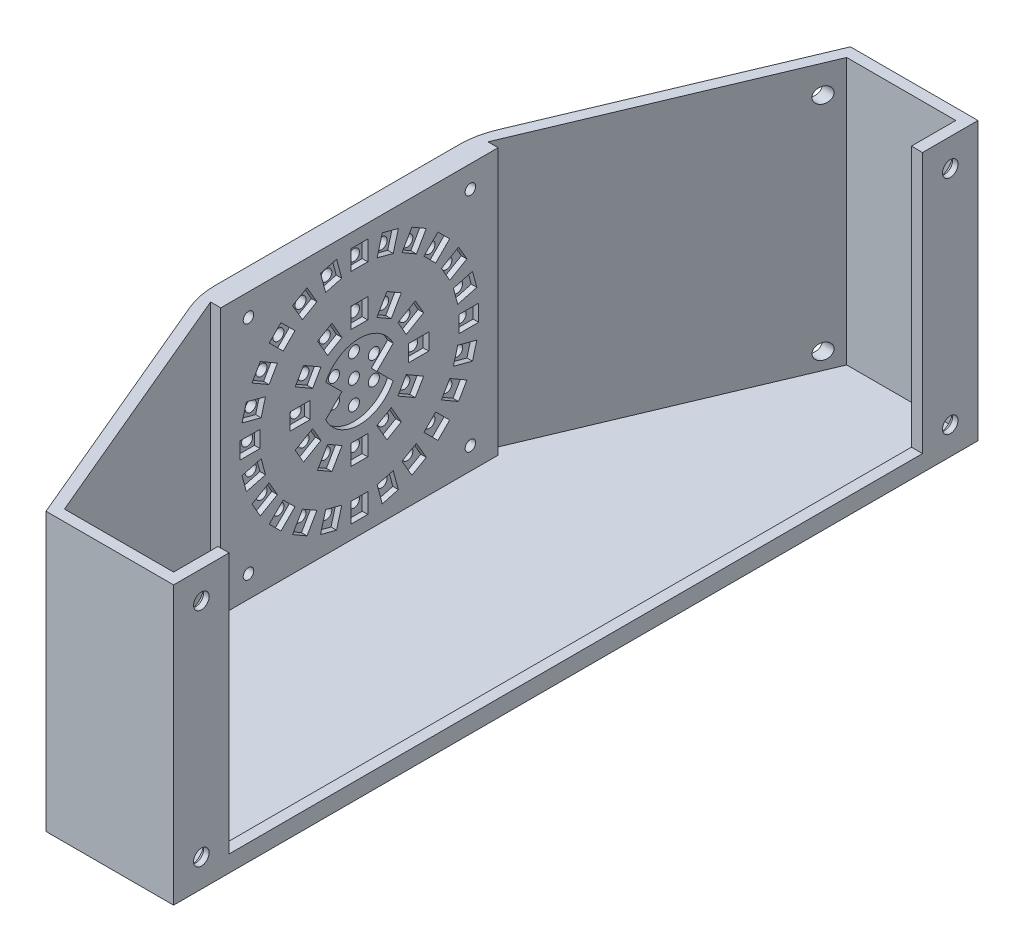
SolidWorks part; units mm, degrees
ref_plane "Спереди" through (0, 0, 0) normal (0, 0, 1) x (1, 0, 0)
ref_plane "Сверху" through (0, 0, 0) normal (0, 1, 0) x (1, 0, 0)
ref_plane "Справа" through (0, 0, 0) normal (1, 0, 0) x (0, 0, -1)
sketch "Эскиз1" plane through (0, 0, 0) normal (0, 1, 0) x (1, 0, 0)
  line L0 (0, 159.887) -> (0, 0) construction
  line L1 (0, 0) -> (281.7797, 0) construction
  line L2 (-60, -50) -> (-60, 50)
  line L3 (-20, -145) -> (20, -145)
  line L5 (-20, 145) -> (20, 145)
  line L6 (20, -145) -> (20, 145)
  line L7 (0, 145) -> (0, -145) construction
  line L8 (-435.8276, 0) -> (20, 0) construction
  line L9 (-60, 50) -> (-20, 145)
  line L10 (-60, -50) -> (-20, -145)
  point P10 (-60, 0)
  dimension "D1" = 290
  dimension "D2" = 40
  dimension "D3" = 100
  dimension "D4" = 80
extrude "Бобышка-Вытянуть1" add sketch "Эскиз1" along normal blind 4
sketch "Эскиз2" plane through (0, 0, 0) normal (0, 1, 0) x (1, 0, 0)
  line L1 (20, 145) -> (26, 145)
  line L2 (20, 145) -> (20, -145)
  line L3 (20, -145) -> (26, -145)
  line L4 (26, 145) -> (26, -145)
  dimension "D1" = 290
  dimension "D2" = 6
extrude "Бобышка-Вытянуть2" add sketch "Эскиз2" along normal blind 4
sketch "Эскиз17" plane through (0, 4, 0) normal (0, 1, 0) x (1, 0, 0)
  line L0 (-20, 145) -> (-60, 50)
  line L1 (-60, 50) -> (-60, -50)
  line L2 (-60, -50) -> (-20, -145)
  line L3 (-20, -145) -> (26, -145)
  line L4 (26, -145) -> (26, 145)
  line L5 (26, 145) -> (-20, 145)
extrude "Вытянуть-Тонкостенный1" add sketch "Эскиз17" along normal blind 96 thin thin type one direction reverse wall 4
sketch "Эскиз29" plane through (0, 100, 0) normal (0, 1, 0) x (1, 0, 0)
  line L1 (-60, 50) -> (-52, 50)
  line L2 (-60, 50) -> (-60, -50)
  line L3 (-60, -50) -> (-52, -50)
  line L4 (-52, 50) -> (-52, -50)
  dimension "D1" = 8
extrude "Бобышка-Вытянуть5" add sketch "Эскиз29" against normal blind 96
sketch "Эскиз20" plane through (-52, 0, 0) normal (1, 0, 0) x (0, 0, -1)
  line L0 (8.2314, 94.3113) -> (6.3873, 87.4288)
  line L1 (6.3, 52) -> (12.1612, 57.8612)
  line L10 (0, 0) -> (0, 100) construction
  line L12 (-48.7884, 52) -> (48.7884, 52) construction
  line L15 (-3, 95) -> (3, 95)
  line L16 (-3, 95) -> (-3, 87.8748)
  line L17 (-3, 87.8748) -> (3, 87.8748)
  line L18 (3, 95) -> (3, 87.8748)
  line L19 (0, 87.8748) -> (0, 95) construction
  line L20 (-3, 91.4374) -> (3, 91.4374) construction
  line L21 (8.2314, 94.3113) -> (14.027, 92.7584)
  line L22 (14.027, 92.7584) -> (12.1829, 85.8759)
  line L23 (6.3873, 87.4288) -> (12.1829, 85.8759)
  line L24 (18.9019, 90.7391) -> (15.3393, 84.5685)
  line L25 (18.9019, 90.7391) -> (24.0981, 87.7391)
  line L26 (24.0981, 87.7391) -> (20.5355, 81.5685)
  line L27 (15.3393, 84.5685) -> (20.5355, 81.5685)
  line L28 (28.2843, 84.5269) -> (23.246, 79.4886)
  line L29 (28.2843, 84.5269) -> (32.5269, 80.2843)
  line L30 (32.5269, 80.2843) -> (27.4886, 75.246)
  line L31 (23.246, 79.4886) -> (27.4886, 75.246)
  line L32 (35.7391, 76.0981) -> (29.5685, 72.5355)
  line L33 (35.7391, 76.0981) -> (38.7391, 70.9019)
  line L34 (38.7391, 70.9019) -> (32.5685, 67.3393)
  line L35 (29.5685, 72.5355) -> (32.5685, 67.3393)
  line L36 (40.7584, 66.027) -> (33.8759, 64.1829)
  line L37 (40.7584, 66.027) -> (42.3113, 60.2314)
  line L38 (42.3113, 60.2314) -> (35.4288, 58.3873)
  line L39 (33.8759, 64.1829) -> (35.4288, 58.3873)
  line L40 (43, 55) -> (35.8748, 55)
  line L41 (43, 55) -> (43, 49)
  line L42 (43, 49) -> (35.8748, 49)
  line L43 (35.8748, 55) -> (35.8748, 49)
  line L44 (42.3113, 43.7686) -> (35.4288, 45.6127)
  line L45 (42.3113, 43.7686) -> (40.7584, 37.973)
  line L46 (40.7584, 37.973) -> (33.8759, 39.8171)
  line L47 (35.4288, 45.6127) -> (33.8759, 39.8171)
  line L48 (38.7391, 33.0981) -> (32.5685, 36.6607)
  line L49 (38.7391, 33.0981) -> (35.7391, 27.9019)
  line L50 (35.7391, 27.9019) -> (29.5685, 31.4645)
  line L51 (32.5685, 36.6607) -> (29.5685, 31.4645)
  line L52 (32.5269, 23.7157) -> (27.4886, 28.754)
  line L53 (32.5269, 23.7157) -> (28.2843, 19.4731)
  line L54 (28.2843, 19.4731) -> (23.246, 24.5114)
  line L55 (27.4886, 28.754) -> (23.246, 24.5114)
  line L56 (24.0981, 16.2609) -> (20.5355, 22.4315)
  line L57 (24.0981, 16.2609) -> (18.9019, 13.2609)
  line L58 (18.9019, 13.2609) -> (15.3393, 19.4315)
  line L59 (20.5355, 22.4315) -> (15.3393, 19.4315)
  line L60 (14.027, 11.2416) -> (12.1829, 18.1241)
  line L61 (14.027, 11.2416) -> (8.2314, 9.6887)
  line L62 (8.2314, 9.6887) -> (6.3873, 16.5712)
  line L63 (12.1829, 18.1241) -> (6.3873, 16.5712)
  line L64 (3, 9) -> (3, 16.1252)
  line L65 (3, 9) -> (-3, 9)
  line L66 (-3, 9) -> (-3, 16.1252)
  line L67 (3, 16.1252) -> (-3, 16.1252)
  line L68 (-8.2314, 9.6887) -> (-6.3873, 16.5712)
  line L69 (-8.2314, 9.6887) -> (-14.027, 11.2416)
  line L70 (-14.027, 11.2416) -> (-12.1829, 18.1241)
  line L71 (-6.3873, 16.5712) -> (-12.1829, 18.1241)
  line L72 (-18.9019, 13.2609) -> (-15.3393, 19.4315)
  line L73 (-18.9019, 13.2609) -> (-24.0981, 16.2609)
  line L74 (-24.0981, 16.2609) -> (-20.5355, 22.4315)
  line L75 (-15.3393, 19.4315) -> (-20.5355, 22.4315)
  line L76 (-28.2843, 19.4731) -> (-23.246, 24.5114)
  line L77 (-28.2843, 19.4731) -> (-32.5269, 23.7157)
  line L78 (-32.5269, 23.7157) -> (-27.4886, 28.754)
  line L79 (-23.246, 24.5114) -> (-27.4886, 28.754)
  line L80 (-35.7391, 27.9019) -> (-29.5685, 31.4645)
  line L81 (-35.7391, 27.9019) -> (-38.7391, 33.0981)
  line L82 (-38.7391, 33.0981) -> (-32.5685, 36.6607)
  line L83 (-29.5685, 31.4645) -> (-32.5685, 36.6607)
  line L84 (-40.7584, 37.973) -> (-33.8759, 39.8171)
  line L85 (-40.7584, 37.973) -> (-42.3113, 43.7686)
  line L86 (-42.3113, 43.7686) -> (-35.4288, 45.6127)
  line L87 (-33.8759, 39.8171) -> (-35.4288, 45.6127)
  line L88 (-43, 49) -> (-35.8748, 49)
  line L89 (-43, 49) -> (-43, 55)
  line L90 (-43, 55) -> (-35.8748, 55)
  line L91 (-35.8748, 49) -> (-35.8748, 55)
  line L92 (-42.3113, 60.2314) -> (-35.4288, 58.3873)
  line L93 (-42.3113, 60.2314) -> (-40.7584, 66.027)
  line L94 (-40.7584, 66.027) -> (-33.8759, 64.1829)
  line L95 (-35.4288, 58.3873) -> (-33.8759, 64.1829)
  line L96 (-38.7391, 70.9019) -> (-32.5685, 67.3393)
  line L97 (-38.7391, 70.9019) -> (-35.7391, 76.0981)
  line L98 (-35.7391, 76.0981) -> (-29.5685, 72.5355)
  line L99 (-32.5685, 67.3393) -> (-29.5685, 72.5355)
  line L100 (-32.5269, 80.2843) -> (-27.4886, 75.246)
  line L101 (-32.5269, 80.2843) -> (-28.2843, 84.5269)
  line L102 (-28.2843, 84.5269) -> (-23.246, 79.4886)
  line L103 (-27.4886, 75.246) -> (-23.246, 79.4886)
  line L104 (-24.0981, 87.7391) -> (-20.5355, 81.5685)
  line L105 (-24.0981, 87.7391) -> (-18.9019, 90.7391)
  line L106 (-18.9019, 90.7391) -> (-15.3393, 84.5685)
  line L107 (-20.5355, 81.5685) -> (-15.3393, 84.5685)
  line L108 (-14.027, 92.7584) -> (-12.1829, 85.8759)
  line L109 (-14.027, 92.7584) -> (-8.2314, 94.3113)
  line L110 (-8.2314, 94.3113) -> (-6.3873, 87.4288)
  line L111 (-12.1829, 85.8759) -> (-6.3873, 87.4288)
  line L112 (6.276, 68.8704) -> (9.9019, 75.1506)
  line L113 (-3, 69.7482) -> (3, 69.7482)
  line L114 (-3, 69.7482) -> (-3, 77)
  line L115 (-3, 77) -> (3, 77)
  line L116 (3, 69.7482) -> (3, 77)
  line L117 (0, 77) -> (0, 69.7482) construction
  line L118 (-3, 73.3741) -> (3, 73.3741) construction
  line L119 (6.276, 68.8704) -> (11.4722, 65.8704)
  line L120 (11.4722, 65.8704) -> (15.0981, 72.1506)
  line L121 (9.9019, 75.1506) -> (15.0981, 72.1506)
  line L122 (13.8704, 63.4722) -> (20.1506, 67.0981)
  line L123 (13.8704, 63.4722) -> (16.8704, 58.276)
  line L124 (16.8704, 58.276) -> (23.1506, 61.9019)
  line L125 (20.1506, 67.0981) -> (23.1506, 61.9019)
  line L126 (17.7482, 55) -> (25, 55)
  line L127 (17.7482, 55) -> (17.7482, 49)
  line L128 (17.7482, 49) -> (25, 49)
  line L129 (25, 55) -> (25, 49)
  line L130 (16.8704, 45.724) -> (23.1506, 42.0981)
  line L131 (16.8704, 45.724) -> (13.8704, 40.5278)
  line L132 (13.8704, 40.5278) -> (20.1506, 36.9019)
  line L133 (23.1506, 42.0981) -> (20.1506, 36.9019)
  line L134 (11.4722, 38.1296) -> (15.0981, 31.8494)
  line L135 (11.4722, 38.1296) -> (6.276, 35.1296)
  line L136 (6.276, 35.1296) -> (9.9019, 28.8494)
  line L137 (15.0981, 31.8494) -> (9.9019, 28.8494)
  line L138 (3, 34.2518) -> (3, 27)
  line L139 (3, 34.2518) -> (-3, 34.2518)
  line L140 (-3, 34.2518) -> (-3, 27)
  line L141 (3, 27) -> (-3, 27)
  line L142 (-6.276, 35.1296) -> (-9.9019, 28.8494)
  line L143 (-6.276, 35.1296) -> (-11.4722, 38.1296)
  line L144 (-11.4722, 38.1296) -> (-15.0981, 31.8494)
  line L145 (-9.9019, 28.8494) -> (-15.0981, 31.8494)
  line L146 (-13.8704, 40.5278) -> (-20.1506, 36.9019)
  line L147 (-13.8704, 40.5278) -> (-16.8704, 45.724)
  line L148 (-16.8704, 45.724) -> (-23.1506, 42.0981)
  line L149 (-20.1506, 36.9019) -> (-23.1506, 42.0981)
  line L150 (-17.7482, 49) -> (-25, 49)
  line L151 (-17.7482, 49) -> (-17.7482, 55)
  line L152 (-17.7482, 55) -> (-25, 55)
  line L153 (-25, 49) -> (-25, 55)
  line L154 (-16.8704, 58.276) -> (-23.1506, 61.9019)
  line L155 (-16.8704, 58.276) -> (-13.8704, 63.4722)
  line L156 (-13.8704, 63.4722) -> (-20.1506, 67.0981)
  line L157 (-23.1506, 61.9019) -> (-20.1506, 67.0981)
  line L158 (-11.4722, 65.8704) -> (-15.0981, 72.1506)
  line L159 (-11.4722, 65.8704) -> (-6.276, 68.8704)
  line L160 (-6.276, 68.8704) -> (-9.9019, 75.1506)
  line L161 (-15.0981, 72.1506) -> (-9.9019, 75.1506)
  line L162 (6.3, 52) -> (12.1612, 46.1388)
  line L163 (-6.3, 52) -> (-12.1612, 57.8612)
  line L164 (-6.3, 52) -> (-12.1612, 46.1388)
  circle A0 centre (0, 52) radius 36 construction
  circle A1 centre (0, 52) radius 43 construction
  circle A3 centre (0, 52) radius 25 construction
  circle A4 centre (0, 52) radius 18 construction
  circle A5 centre (0, 52) radius 13.5 construction
  arc A6 (-12.1612, 57.8612) -> (12.1612, 57.8612) centre (0, 52) cw
  arc A7 (-12.1612, 46.1388) -> (12.1612, 46.1388) centre (0, 52) ccw
  point P15 (0, 91.4374)
  point P21 (0, 73.3741)
  point P112 (0, 52)
  point P163 (0, 52)
  dimension "D1" = 72
  dimension "D2" = 86
  dimension "D3" = 50
  dimension "D5" = 36
  dimension "D7" = 27
  dimension "D4" = 6
  dimension "D6" = 6
  dimension "D8" = 6.3
  dimension "D9" = 90
extrude "Вырез-Вытянуть7" cut sketch "Эскиз20" against normal blind 2
sketch "Эскиз16" plane through (26, 0, 0) normal (1, 0, 0) x (0, 0, -1)
  line L0 (0, 111.0778) -> (0, 40) construction
  line L1 (-145, 0) -> (145, 0) construction
  line L3 (145, 100) -> (145, 0) construction
  line L4 (-145, 100) -> (145, 100) construction
  circle A2 centre (135, 90) radius 2.8
  circle A5 centre (135, 10) radius 2.8
  circle A6 centre (-135, 90) radius 2.8
  circle A7 centre (-135, 10) radius 2.8
  dimension "D2" = 5.6
  dimension "D3" = 10
  dimension "D4" = 10
  dimension "D5" = 10
  dimension "D1" = 10
extrude "Вырез-Вытянуть6" cut sketch "Эскиз16" against normal through all both and the other way through all
sketch "Эскиз21" plane through (-52, 0, 0) normal (1, 0, 0) x (0, 0, -1)
  line L0 (48.7884, 52) -> (-48.7884, 52) construction
  line L3 (0, 100) -> (0, 0) construction
  circle A0 centre (0, 52) radius 38.5 construction
  circle A1 centre (0, 90.5) radius 2
  circle A2 centre (9.9645, 89.1881) radius 2
  circle A3 centre (19.25, 85.342) radius 2
  circle A4 centre (27.2236, 79.2236) radius 2
  circle A5 centre (33.342, 71.25) radius 2
  circle A6 centre (37.1881, 61.9645) radius 2
  circle A7 centre (38.5, 52) radius 2
  circle A8 centre (37.1881, 42.0355) radius 2
  circle A9 centre (33.342, 32.75) radius 2
  circle A10 centre (27.2236, 24.7764) radius 2
  circle A11 centre (19.25, 18.658) radius 2
  circle A12 centre (9.9645, 14.8119) radius 2
  circle A13 centre (0, 13.5) radius 2
  circle A14 centre (-9.9645, 14.8119) radius 2
  circle A15 centre (-19.25, 18.658) radius 2
  circle A16 centre (-27.2236, 24.7764) radius 2
  circle A17 centre (-33.342, 32.75) radius 2
  circle A18 centre (-37.1881, 42.0355) radius 2
  circle A19 centre (-38.5, 52) radius 2
  circle A20 centre (-37.1881, 61.9645) radius 2
  circle A21 centre (-33.342, 71.25) radius 2
  circle A22 centre (-27.2236, 79.2236) radius 2
  circle A23 centre (-19.25, 85.342) radius 2
  circle A24 centre (-9.9645, 89.1881) radius 2
  circle A25 centre (0, 52) radius 21 construction
  circle A26 centre (0, 73) radius 2
  circle A27 centre (10.5, 70.1865) radius 2
  circle A28 centre (18.1865, 62.5) radius 2
  circle A29 centre (21, 52) radius 2
  circle A30 centre (18.1865, 41.5) radius 2
  circle A31 centre (10.5, 33.8135) radius 2
  circle A32 centre (0, 31) radius 2
  circle A33 centre (-10.5, 33.8135) radius 2
  circle A34 centre (-18.1865, 41.5) radius 2
  circle A35 centre (-21, 52) radius 2
  circle A36 centre (-18.1865, 62.5) radius 2
  circle A37 centre (-10.5, 70.1865) radius 2
  circle A38 centre (0, 52) radius 8.3 construction
  circle A39 centre (0, 60.3) radius 2
  circle A40 centre (7.188, 56.15) radius 2
  circle A41 centre (7.188, 47.85) radius 2
  circle A42 centre (0, 43.7) radius 2
  circle A43 centre (-7.188, 47.85) radius 2
  circle A44 centre (-7.188, 56.15) radius 2
  circle A45 centre (0, 52) radius 2
  point P64 (0, 52)
  point P90 (0, 52)
  point P104 (0, 52)
  dimension "D1" = 77
  dimension "D2" = 4
  dimension "D3" = 42
  dimension "D4" = 4
  dimension "D5" = 16.6
  dimension "D6" = 4
extrude "Отверстия под LED" cut sketch "Эскиз21" against normal blind 10 contours A1
fillet "Скругление3" radius 30 2 edges at (-60, 50, 50) (-60, 50, -50)
chamfer "Фаска2" distance 2 angle 45 24 edges at (-60, 71.25, 31.342) (-60, 61.9645, 35.1881) (-60, 52, 36.5) (-60, 42.0355, 35.1881) (-60, 32.75, 31.342) (-60, 24.7764, 25.2236) (-60, 18.658, 17.25) (-60, 14.8119, 7.9645) (-60, 13.5, -2) (-60, 14.8119, -11.9645) (-60, 18.658, -21.25) (-60, 24.7764, -29.2236) (-60, 32.75, -35.342) (-60, 42.0355, -39.1881) (-60, 52, -40.5) (-60, 61.9645, -39.1881) (-60, 71.25, -35.342) (-60, 79.2236, -29.2236) (-60, 85.342, -21.25) (-60, 89.1881, -11.9645) (-60, 90.5, -2) (-60, 79.2236, 25.2236) (-60, 85.342, 17.25) (-60, 89.1881, 7.9645)
sketch "Эскиз30" plane through (-52, 0, 0) normal (1, 0, 0) x (0, 0, -1)
  line L1 (-40, 12) -> (40, 12) construction
  line L2 (-40, 12) -> (-40, 92) construction
  line L3 (-40, 92) -> (40, 92) construction
  line L4 (40, 12) -> (40, 92) construction
  line L5 (0, 92) -> (0, 12) construction
  line L6 (-40, 52) -> (40, 52) construction
  circle A0 centre (-40, 92) radius 1.9
  circle A1 centre (40, 92) radius 1.9
  circle A2 centre (-40, 12) radius 1.9
  circle A3 centre (40, 12) radius 1.9
  point P0 (0, 52)
  dimension "D3" = 3.8
  dimension "D1" = 80
  dimension "D2" = 80
extrude "Вырез-Вытянуть11" cut sketch "Эскиз30" against normal blind 7
chamfer "Фаска3" distance 2 angle 45 7 edges at (-60, 47.85, 5.188) (-60, 43.7, -2) (-60, 47.85, -9.188) (-60, 56.15, -9.188) (-60, 52, -2) (-60, 56.15, 5.188) (-60, 60.3, -2)
chamfer "Фаска4" distance 2 angle 45 12 edges at (-60, 52, 19) (-60, 41.5, 16.1865) (-60, 33.8135, 8.5) (-60, 31, -2) (-60, 33.8135, -12.5) (-60, 41.5, -20.1865) (-60, 52, -23) (-60, 62.5, -20.1865) (-60, 70.1865, -12.5) (-60, 73, -2) (-60, 70.1865, 8.5) (-60, 62.5, 16.1865)
chamfer "Фаска6" distance 2 angle 45 4 edges at (22, 10, -132.2) (22, 10, 137.8) (22, 90, 137.8) (22, 90, -132.2)
sketch "Эскиз34" plane through (26, 0, 0) normal (1, 0, 0) x (0, 0, -1)
  line L0 (-145, 100) -> (145, 100) construction
  line L1 (-125, 6) -> (125, 6)
  line L2 (-125, 6) -> (-125, 100)
  line L3 (-125, 100) -> (125, 100)
  line L4 (125, 6) -> (125, 100)
  line L5 (0, 100) -> (0, 6) construction
  line L6 (-125, 53) -> (125, 53) construction
  line L7 (145, 100) -> (145, 0) construction
  line L8 (-145, 0) -> (145, 0) construction
  point P0 (0, 53)
  dimension "D1" = 20
  dimension "D2" = 6
extrude "Вырез-Вытянуть12" cut sketch "Эскиз34" against normal blind 10
